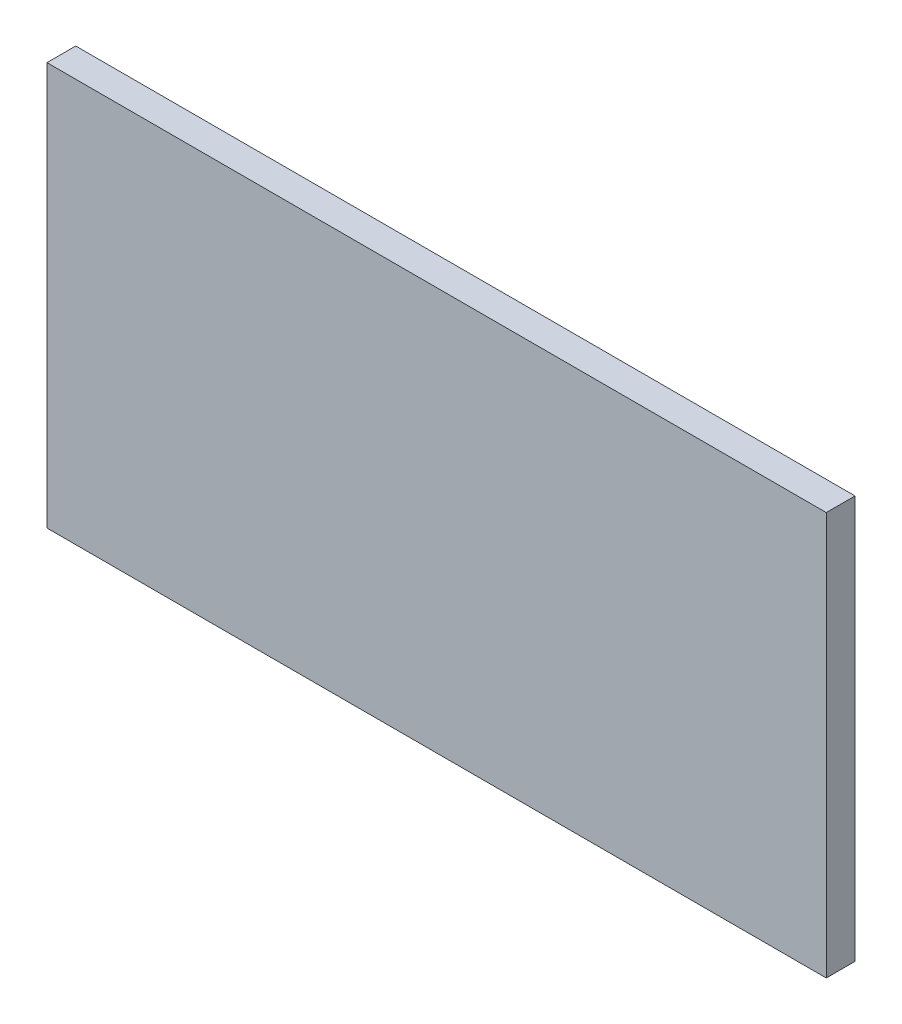
SolidWorks part; units mm, degrees
ref_plane "Front" through (0, 0, 0) normal (0, 0, 1) x (1, 0, 0)
ref_plane "Top" through (0, 0, 0) normal (0, 1, 0) x (1, 0, 0)
ref_plane "Right" through (0, 0, 0) normal (1, 0, 0) x (0, 0, -1)
sketch "Sketch1" plane through (0, 0, 0) normal (0, 0, 1) x (1, 0, 0)
  line L1 (0, 0) -> (40.6, 0)
  line L2 (0, 0) -> (0, 21)
  line L3 (0, 21) -> (40.6, 21)
  line L4 (40.6, 0) -> (40.6, 21)
  dimension "D1" = 21
  dimension "D2" = 40.6
extrude "Boss-Extrude1" add sketch "Sketch1" along normal blind 1.5 contours L3 L4 L1 L2
sketch "Sketch2" plane through (0, 0, 0) normal (0, 0, -1) x (-1, 0, 0)
  line L1 (-6.4, 12.4) -> (-10.16, 12.4)
  line L2 (-6.4, 12.4) -> (-6.4, 15.4)
  line L3 (-6.4, 15.4) -> (-10.16, 15.4)
  line L4 (-10.16, 12.4) -> (-10.16, 15.4)
  line L5 (0, 0) -> (0, 21) construction
  line L6 (0, 21) -> (-40.6, 21) construction
  dimension "D1" = 6.4
  dimension "3.7" = 3.76
  dimension "D3" = 3
  dimension "D4" = 5.6
extrude "Boss-Extrude3" add sketch "Sketch2" along normal blind 1.1
sketch "Sketch3" plane through (0, 0, -1.1) normal (0, 0, -1) x (-1, 0, 0)
  line L0 (-10.16, 13.9) -> (-6.4, 13.9) construction
  line L1 (-10.16, 15.4) -> (-10.16, 12.4) construction
  line L2 (-6.4, 12.4) -> (-6.4, 15.4) construction
  line L3 (-10.16, 12.4) -> (-6.4, 12.4) construction
  circle A0 centre (-8.98, 13.9) radius 0.25
  dimension "D1" = 1.5
  dimension "D3" = 0.5
  dimension "D2" = 1.18
extrude "Cut-Extrude1" cut sketch "Sketch3" against normal blind 0.5 contours A0
fillet "Fillet3" radius 0.5 4 edges at (10.16, 13.9, -1.1) (8.28, 15.4, -1.1) (6.4, 13.9, -1.1) (8.28, 12.4, -1.1)
sketch "Sketch4" plane through (0, 0, 0) normal (0, 0, -1) x (-1, 0, 0)
  line L0 (0, 0) -> (0, 21) construction
  line L1 (0, 21) -> (-40.6, 21) construction
  circle A0 centre (-18.925, 3.72) radius 0.65
  circle A1 centre (-20.675, 3.72) radius 0.65
  circle A2 centre (-20.675, 5.47) radius 0.65
  circle A3 centre (-20.675, 7.22) radius 0.65
  circle A4 centre (-18.925, 5.47) radius 0.65
  circle A5 centre (-18.925, 7.22) radius 0.65
  dimension "D1" = 18.925
  dimension "D4" = 1.3
  dimension "D5" = 17.28
  dimension "D2" = 2
  dimension "D3" = 3
extrude "Boss-Extrude4" add sketch "Sketch4" along normal blind 0.25
